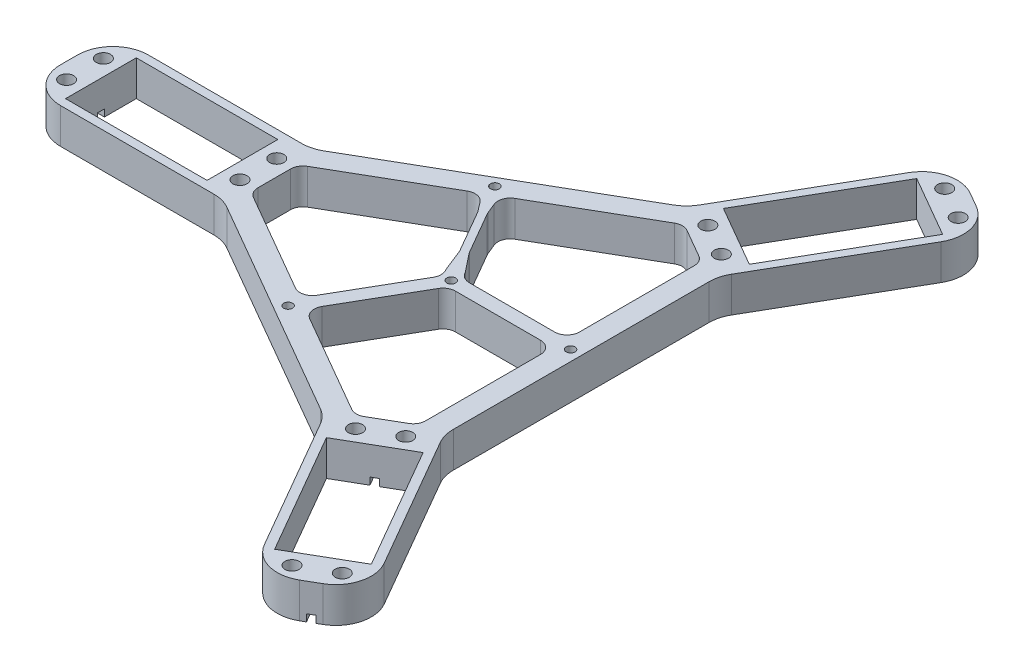
SolidWorks part; units mm, degrees
ref_plane "Front Plane" through (0, 0, 0) normal (0, 0, 1) x (1, 0, 0)
ref_plane "Top Plane" through (0, 0, 0) normal (0, 1, 0) x (1, 0, 0)
ref_plane "Right Plane" through (0, 0, 0) normal (1, 0, 0) x (0, 0, -1)
sketch "Sketch1" plane through (0, 0, 0) normal (0, 1, 0) x (1, 0, 0)
  line L0 (0, 10) -> (40, 10) construction
  line L1 (0, 0) -> (40, 0)
  line L2 (0, 0) -> (0, 20)
  line L3 (0, 20) -> (40, 20)
  line L4 (40, 0) -> (40, 20)
  line L5 (0, 20) -> (-4.5, 20)
  line L6 (-9, -2.4) -> (49, -2.4)
  line L7 (-9, -2.4) -> (-9, 22.4)
  line L8 (-9, 22.4) -> (49, 22.4)
  line L9 (49, -2.4) -> (49, 22.4)
  line L10 (-9, -2.4) -> (49, 22.4) construction
  line L11 (-9, 22.4) -> (49, -2.4) construction
  line L12 (-4.5, 20) -> (-4.5, 15.2)
  line L13 (20, 20) -> (20, 0) construction
  line L14 (49, 10) -> (130.7387, 10)
  line L15 (139.8397, 100.7365) -> (119.8397, 66.0955)
  line L16 (139.8397, 100.7365) -> (157.1603, 90.7365)
  line L17 (157.1603, 90.7365) -> (137.1603, 56.0955)
  line L18 (119.8397, 66.0955) -> (137.1603, 56.0955)
  line L19 (157.1603, 90.7365) -> (159.4103, 94.6336)
  line L20 (142.2613, 109.7307) -> (113.2613, 59.5013)
  line L21 (142.2613, 109.7307) -> (163.7387, 97.3307)
  line L22 (163.7387, 97.3307) -> (134.7387, 47.1013)
  line L23 (113.2613, 59.5013) -> (134.7387, 47.1013)
  line L24 (159.4103, 94.6336) -> (155.2533, 97.0336)
  line L25 (124, 53.3013) -> (83.1306, -17.4865)
  line L26 (148.5, 95.7365) -> (128.5, 61.0955) construction
  line L27 (142.2613, 109.7307) -> (134.7387, 47.1013) construction
  line L28 (163.7387, 97.3307) -> (113.2613, 59.5013) construction
  line L29 (147.1603, 73.416) -> (129.8397, 83.416) construction
  line L30 (157.1603, -70.7365) -> (137.1603, -36.0955)
  line L31 (157.1603, -70.7365) -> (139.8397, -80.7365)
  line L32 (139.8397, -80.7365) -> (119.8397, -46.0955)
  line L33 (137.1603, -36.0955) -> (119.8397, -46.0955)
  line L34 (139.8397, -80.7365) -> (142.0897, -84.6336)
  line L35 (163.7387, -77.3307) -> (134.7387, -27.1013)
  line L36 (163.7387, -77.3307) -> (142.2613, -89.7307)
  line L37 (142.2613, -89.7307) -> (113.2613, -39.5013)
  line L38 (134.7387, -27.1013) -> (113.2613, -39.5013)
  line L39 (142.0897, -84.6336) -> (146.2467, -82.2336)
  line L40 (124, -33.3013) -> (83.1306, 37.4865)
  line L41 (148.5, -75.7365) -> (128.5, -41.0955) construction
  line L42 (163.7387, -77.3307) -> (113.2613, -39.5013) construction
  line L43 (142.2613, -89.7307) -> (134.7387, -27.1013) construction
  line L44 (129.8397, -63.416) -> (147.1603, -53.416) construction
  line L45 (49, 22.4) -> (113.2613, 59.5013)
  line L46 (134.7387, 47.1013) -> (134.7387, -27.1013)
  line L47 (113.2613, -39.5013) -> (49, -2.4)
  line L48 (49, 17.7812) -> (117.2613, 57.1919)
  line L49 (130.7387, 49.4107) -> (130.7387, -29.4107)
  line L50 (117.2613, -37.1919) -> (49, 2.2188)
  line L51 (51, 18.9359) -> (115.2613, 56.0372) construction
  line L52 (130.7387, 47.1013) -> (130.7387, -27.1013) construction
  line L53 (115.2613, -36.0372) -> (51, 1.0641) construction
  line L54 (122.2679, 54.3013) -> (81.3986, -16.4865)
  line L55 (49, 8) -> (130.7387, 8)
  line L56 (125.7321, -32.3013) -> (99, 14)
  line L57 (125.7321, 52.3013) -> (84.8627, -18.4865)
  line L58 (49, 12) -> (130.7387, 12)
  line L59 (122.2679, -34.3013) -> (95.5359, 12)
  line L60 (49, 12) -> (99, 12) construction
  line L61 (125.7321, -32.3013) -> (100.7321, 11) construction
  line L62 (122.2679, 54.3013) -> (97.2679, 11) construction
  line L63 (122.2679, -34.3013) -> (97.2679, 9) construction
  line L64 (124, 53.3013) -> (99, 10) construction
  line L65 (125.7321, 52.3013) -> (100.7321, 9) construction
  line L66 (124, -33.3013) -> (99, 10) construction
  line L67 (49, 10) -> (99, 10) construction
  line L68 (49, 8) -> (99, 8) construction
  line L69 (83.1306, 37.4865) -> (81.1306, 40.9506) construction
  line L70 (130.7387, 10) -> (134.7387, 10) construction
  line L71 (83.1306, -17.4865) -> (81.1306, -20.9506) construction
  line L72 (47, 22.4) -> (114.2613, 61.2333)
  line L73 (135.7387, 48.8333) -> (135.7387, -28.8333)
  line L74 (129.7387, 49.988) -> (129.7387, -29.988)
  line L75 (49, 16.6265) -> (118.2613, 56.6145)
  line L76 (118.2613, -36.6145) -> (49, 3.3735)
  line L77 (114.2613, -41.2333) -> (47, -2.4)
  line L78 (112.7613, -40.3673) -> (48.5, -3.266) construction
  line L79 (117.7613, -36.3258) -> (49.5, 3.0848) construction
  line L80 (49.5, 16.9152) -> (117.7613, 56.3258) construction
  line L81 (48.5, 23.266) -> (112.7613, 60.3673) construction
  line L82 (129.7387, 49.4107) -> (129.7387, -29.4107) construction
  line L83 (135.7387, 47.1013) -> (135.7387, -27.1013) construction
  line L84 (93.0648, 18.2801) -> (85.9961, 30.5234)
  line L85 (94.7968, 19.2801) -> (87.7282, 31.5234)
  line L86 (124.866, -32.8013) -> (83.9967, 37.9865) construction
  line L87 (123.134, -33.8013) -> (82.2646, 36.9865) construction
  line L89 (85.9961, 30.5234) -> (81.3986, 36.4865)
  line L90 (87.7282, 31.5234) -> (84.8627, 38.4865)
  line L91 (93.0648, 18.2801) -> (95.5359, 12)
  line L92 (94.7968, 19.2801) -> (99, 14)
  line L94 (122.2679, -34.3013) -> (81.3986, 36.4865) construction
  line L96 (125.7321, -32.3013) -> (84.8627, 38.4865) construction
  circle A0 centre (-4.5, 15.2) radius 2
  circle A1 centre (44.5, 15.2) radius 2
  circle A2 centre (44.5, 4.8) radius 2
  circle A3 centre (-4.5, 4.8) radius 2
  circle A4 centre (155.2533, 97.0336) radius 2
  circle A5 centre (130.7533, 54.5984) radius 2
  circle A6 centre (121.7467, 59.7984) radius 2
  circle A7 centre (146.2467, 102.2336) radius 2
  circle A8 centre (146.2467, -82.2336) radius 2
  circle A9 centre (121.7467, -39.7984) radius 2
  circle A10 centre (130.7533, -34.5984) radius 2
  circle A11 centre (155.2533, -77.0336) radius 2
  circle A12 centre (82.1306, -19.2186) radius 1.25
  circle A13 centre (82.1306, 39.2186) radius 1.25
  circle A14 centre (132.7387, 10) radius 1.25
  circle A15 centre (99, 10) radius 1.25
  point P7 (20, 10)
  point P34 (138.5, 78.416)
  point P57 (138.5, -58.416)
  point P74 (99, 10)
  dimension "D7" = 4
  dimension "D8" = 1
  dimension "D1" = 40
  dimension "D2" = 20
  dimension "D3" = 58
  dimension "D4" = 24.8
  dimension "D5" = 4.5
  dimension "D6" = 4.8
  dimension "D10" = 4
  dimension "D11" = 4
  dimension "D12" = 4
  dimension "D13" = 2
  dimension "D14" = 2
  dimension "D15" = 1
  dimension "D16" = 1
  dimension "D17" = 1
  dimension "D18" = 1
  dimension "D19" = 1
  dimension "D20" = 1
  dimension "D21" = 1
  dimension "D9" = 3
extrude "Boss-Extrude1" add sketch "Sketch1" along normal blind 10
sketch "Sketch2" plane through (-9, 0, 0) normal (-1, 0, 0) x (0, 0, 1)
  line L0 (2.4, 0) -> (-22.4, 0) construction
  line L1 (-11, -2) -> (-9, -2)
  line L2 (-11, -2) -> (-11, 2)
  line L3 (-11, 2) -> (-9, 2)
  line L4 (-9, -2) -> (-9, 2)
  line L5 (-11, -2) -> (-9, 2) construction
  line L6 (-11, 2) -> (-9, -2) construction
  point P0 (-10, 0)
  dimension "D1" = 2
  dimension "D2" = 4
extrude "Cut-Extrude1" cut sketch "Sketch2" against normal blind 56
sketch "Sketch3" plane through (74.4199, 0, 128.899) normal (0.5, 0, 0.866) x (0.866, 0, -0.5)
  line L0 (103.1365, 0) -> (78.3365, 0) construction
  line L1 (89.7365, -2) -> (91.7365, -2)
  line L2 (89.7365, -2) -> (89.7365, 2)
  line L3 (89.7365, 2) -> (91.7365, 2)
  line L4 (91.7365, -2) -> (91.7365, 2)
  line L5 (89.7365, -2) -> (91.7365, 2) construction
  line L6 (89.7365, 2) -> (91.7365, -2) construction
  point P0 (90.7365, 0)
  dimension "D1" = 2
  dimension "D2" = 4
extrude "Cut-Extrude2" cut sketch "Sketch3" against normal blind 56
sketch "Sketch4" plane through (83.0801, 0, -143.899) normal (0.5, 0, -0.866) x (-0.866, 0, -0.5)
  line L0 (-68.3365, 0) -> (-93.1365, 0) construction
  line L1 (-81.7365, -2) -> (-79.7365, -2)
  line L2 (-81.7365, -2) -> (-81.7365, 2)
  line L3 (-81.7365, 2) -> (-79.7365, 2)
  line L4 (-79.7365, -2) -> (-79.7365, 2)
  line L5 (-81.7365, -2) -> (-79.7365, 2) construction
  line L6 (-81.7365, 2) -> (-79.7365, -2) construction
  point P0 (-80.7365, 0)
  dimension "D1" = 2
  dimension "D2" = 4
extrude "Cut-Extrude3" cut sketch "Sketch4" against normal blind 56
fillet "Fillet1" radius 10 12 edges at (142.2613, 5, -109.7307) (163.7387, 5, -97.3307) (163.7387, 5, 77.3307) (142.2613, 5, 89.7307) (-9, 5, -22.4) (-9, 5, 2.4) (47, 5, -22.4) (114.2613, 5, -61.2333) (135.7387, 5, -48.8333) (135.7387, 5, 28.8333) (114.2613, 5, 41.2333) (47, 5, 2.4)
fillet "Fillet2" radius 3.5 21 edges at (129.7387, 5, -8) (129.7387, 5, 29.988) (118.2613, 5, 36.6145) (85.3627, 5, 17.6205) (129.7387, 5, -12) (129.7387, 5, -49.988) (118.2613, 5, -56.6145) (49, 5, -3.3735) (81.8986, 5, 15.6205) (85.2467, 5, -37.5535) (87.7282, 5, -31.5234) (94.7968, 5, -19.2801) (99, 5, -14) (100.1547, 5, -12) (96.6906, 5, -10) (95.5359, 5, -12) (93.0648, 5, -18.2801) (85.9961, 5, -30.5234) (82.0146, 5, -35.6875) (49, 5, -16.6265) (100.1547, 5, -8)
